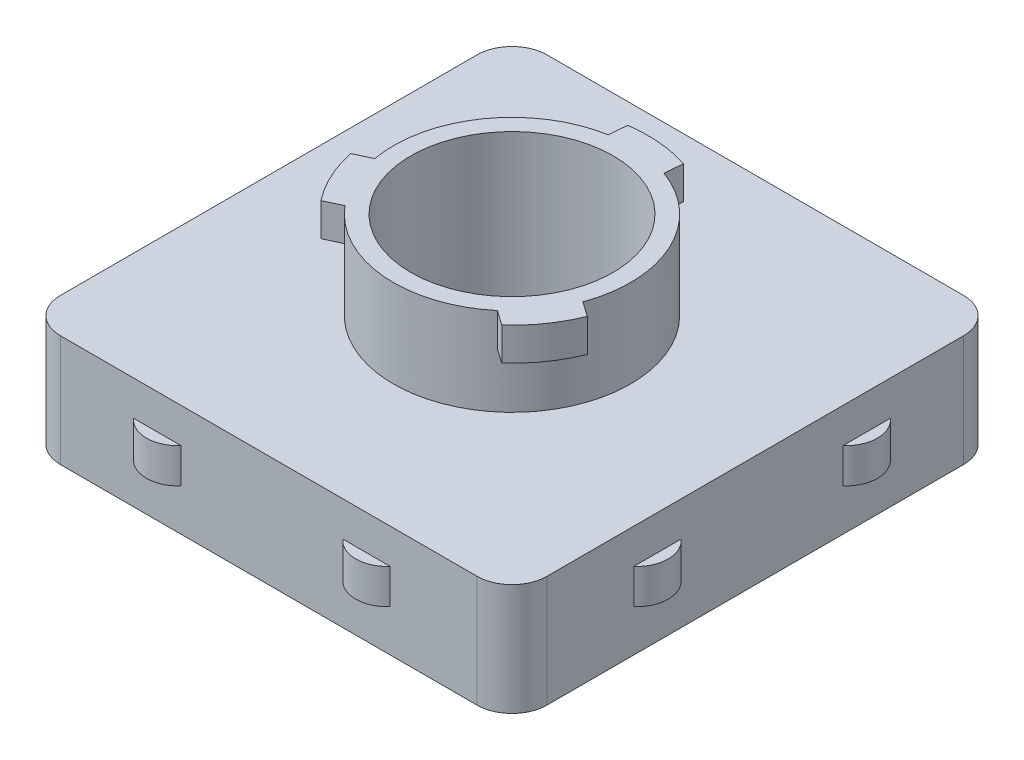
SolidWorks part; units mm, degrees
ref_plane "Front Plane" through (0, 0, 0) normal (0, 0, 1) x (1, 0, 0)
ref_plane "Top Plane" through (0, 0, 0) normal (0, 1, 0) x (1, 0, 0)
ref_plane "Right Plane" through (0, 0, 0) normal (1, 0, 0) x (0, 0, -1)
sketch "Sketch1" plane through (0, 0, 0) normal (0, 1, 0) x (1, 0, 0)
  line L1 (-22.1475, -22.1475) -> (22.1475, -22.1475)
  line L2 (-22.1475, -22.1475) -> (-22.1475, 22.1475)
  line L3 (-22.1475, 22.1475) -> (22.1475, 22.1475)
  line L4 (22.1475, -22.1475) -> (22.1475, 22.1475)
  line L5 (-22.1475, -22.1475) -> (22.1475, 22.1475) construction
  line L6 (-22.1475, 22.1475) -> (22.1475, -22.1475) construction
  point P0 (0, 0)
  dimension "D1" = 44.2951
extrude "Boss-Extrude1" add sketch "Sketch1" along normal blind 10.16
sketch "Sketch2" plane through (0, 10.16, 0) normal (0, 1, 0) x (1, 0, 0)
  line L4 (22.1475, -22.1475) -> (22.1475, 22.1475)
  line L5 (22.1475, 22.1475) -> (-22.1475, 22.1475)
  line L6 (-22.1475, 22.1475) -> (-22.1475, -22.1475)
  line L7 (-22.1475, -22.1475) -> (22.1475, -22.1475)
  line L8 (22.1475, -22.1475) -> (22.1475, 22.1475)
  line L9 (22.1475, 22.1475) -> (-22.1475, 22.1475)
  line L10 (-22.1475, 22.1475) -> (-22.1475, -22.1475)
  line L11 (-22.1475, -22.1475) -> (22.1475, -22.1475)
  circle A0 centre (0, 0) radius 10.795
  circle A1 centre (0, 0) radius 9.2075
  point P7 (0, 8.0979)
  dimension "D2" = 21.59
  dimension "D3" = 18.415
  dimension "D1" = 0
extrude "Boss-Extrude2" add sketch "Sketch2" along normal blind 8 contours A0 A1
sketch "Sketch5" plane through (0, 18.16, 0) normal (0, 1, 0) x (1, 0, 0)
  line L0 (2.794, -12.072) -> (2.794, -10.4272)
  line L1 (-2.794, -12.072) -> (-2.794, -10.4272)
  line L2 (0, 0) -> (10.1502, -7.1072) construction
  line L3 (0, 0) -> (0, -12.3911) construction
  line L4 (8.2862, -9.2129) -> (6.9389, -8.2695)
  line L5 (11.4914, -4.6355) -> (10.144, -3.6921)
  circle A0 centre (0, 0) radius 10.795 construction
  circle A1 centre (0, 0) radius 10.795
  arc A2 (2.794, -12.072) -> (-2.794, -12.072) centre (0, 0) cw
  arc A3 (8.2862, -9.2129) -> (11.4914, -4.6355) centre (0, 0) ccw
  point P5 (0, -12.3911)
  circle M5 centre (0, 0) radius 10.795
  dimension "D1" = 12.3911
  dimension "D2" = 5.588
  dimension "D3" = 55
  dimension "D4" = 5.588
extrude "Boss-Extrude3" add sketch "Sketch5" against normal blind 3 contours L4 A3 L5 M5
pattern_circular "CirPattern1" count 3 over 360 about axis through (0, 0, 0) along (0, 1, 0) of "Boss-Extrude3"
sketch "Sketch6" plane through (0, 10.16, 0) normal (0, 1, 0) x (1, 0, 0)
  line L0 (22.1475, 22.1475) -> (-22.1475, 22.1475) construction
  line L1 (-22.1475, -22.1475) -> (22.1475, -22.1475) construction
  line L2 (22.1475, 22.1475) -> (-22.1475, 22.1475)
  line L3 (-22.1475, -22.1475) -> (22.1475, -22.1475)
  line L4 (-12.3065, -23.125) -> (-7.9885, -23.125) construction
  line L5 (-12.3065, 23.125) -> (-7.9885, 23.125) construction
  line L6 (-22.1475, 22.1475) -> (-22.1475, -22.1475) construction
  line L7 (-12.3065, -22.1475) -> (-7.9885, -22.1475)
  line L8 (-12.3065, 22.1475) -> (-7.9885, 22.1475)
  arc A0 (-12.3065, -22.1475) -> (-7.9885, -22.1475) centre (-10.1475, -20.2519) ccw
  arc A1 (-12.3065, 22.1475) -> (-7.9885, 22.1475) centre (-10.1475, 20.2519) cw
  dimension "D1" = 46.25
  dimension "D2" = 12
  dimension "D3" = 4.318
extrude "Boss-Extrude4" add sketch "Sketch6" against normal blind 6.35 contours A1 L2 | L3 A0
sketch "Sketch7" plane through (0, 10.16, 0) normal (0, 1, 0) x (1, 0, 0)
  line L0 (-7.9885, 22.1475) -> (-12.3065, 22.1475) construction
  line L1 (-12.3065, -22.1475) -> (-7.9885, -22.1475) construction
  line L2 (-7.9885, 22.1475) -> (-12.3065, 22.1475)
  line L3 (-12.3065, -22.1475) -> (-7.9885, -22.1475)
  arc A0 (-7.9885, 22.1475) -> (-12.3065, 22.1475) centre (-10.1475, 20.2519) ccw construction
  arc A1 (-12.3065, -22.1475) -> (-7.9885, -22.1475) centre (-10.1475, -20.2519) ccw construction
  arc A2 (-7.9885, 22.1475) -> (-12.3065, 22.1475) centre (-10.1475, 20.2519) ccw
  arc A3 (-12.3065, -22.1475) -> (-7.9885, -22.1475) centre (-10.1475, -20.2519) ccw
extrude "Cut-Extrude1" cut sketch "Sketch7" against normal blind 3.175
pattern_linear "LPattern1" count 2 spacing 19.05 along (1, 0, 0) of "Boss-Extrude4", "Cut-Extrude1"
fillet "Fillet1" radius 3.175 4 edges at (-22.1475, 5.08, 22.1475) (-22.1475, 5.08, -22.1475) (22.1475, 5.08, -22.1475) (22.1475, 5.08, 22.1475)
sketch "Sketch12" plane through (0, 0, 0) normal (0, 0, 1) x (1, 0, 0)
  line L0 (0, 0) -> (0, 19.1869) construction
pattern_circular "CirPattern2" count 2 over 90 about axis through (0, 0, 0) along (0, 1, 0) of "LPattern1", "Cut-Extrude1", "Boss-Extrude4"
sketch "Sketch13" plane through (0, 10.16, 0) normal (0, 1, 0) x (1, 0, 0)
  circle A0 centre (0, 0) radius 9.2075 construction
  circle A1 centre (0, 0) radius 9.2075
extrude "Cut-Extrude2" cut sketch "Sketch13" against normal through all
